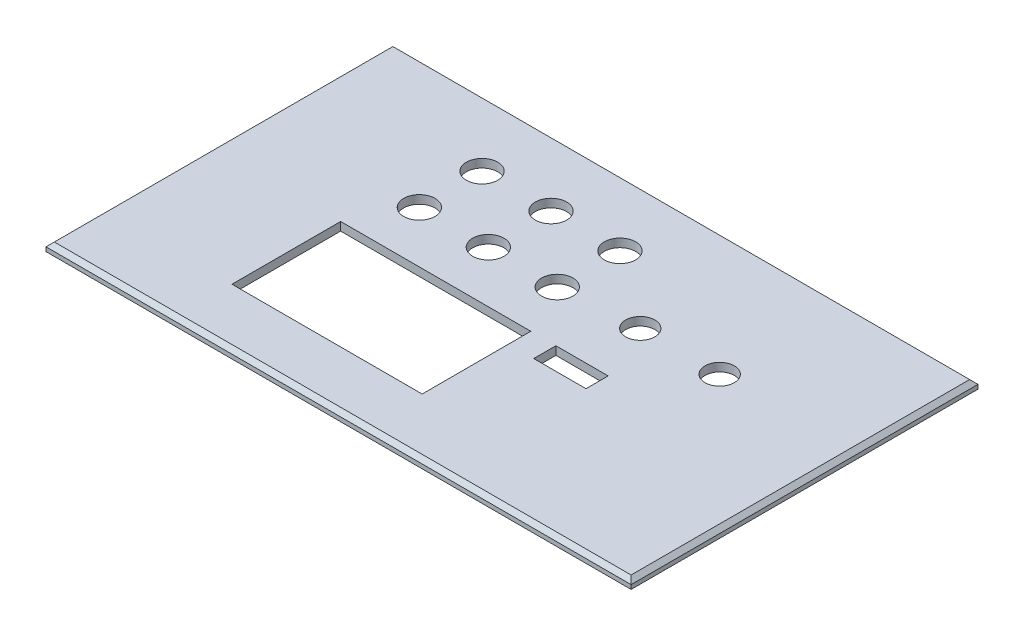
SolidWorks part; units mm, degrees
ref_plane "Front Plane" through (0, 0, 0) normal (0, 0, 1) x (1, 0, 0)
ref_plane "Top Plane" through (0, 0, 0) normal (0, 1, 0) x (1, 0, 0)
ref_plane "Right Plane" through (0, 0, 0) normal (1, 0, 0) x (0, 0, -1)
sketch "Sketch2" plane through (0, 0, 0) normal (0, 1, 0) x (1, 0, 0)
  line L1 (-53.6564, 31.1454) -> (-193.6564, 31.1454)
  line L2 (-53.6564, 31.1454) -> (-53.6564, -51.8546)
  line L3 (-53.6564, -51.8546) -> (-193.6564, -51.8546)
  line L4 (-193.6564, 31.1454) -> (-193.6564, -51.8546)
  line L13 (-162.6564, -38.3546) -> (-117.1564, -38.3546)
  line L14 (-162.6564, -38.3546) -> (-162.6564, -12.3546)
  line L15 (-162.6564, -12.3546) -> (-117.1564, -12.3546)
  line L16 (-117.1564, -38.3546) -> (-117.1564, -12.3546)
  line L19 (-98.6564, -17.6508) -> (-111.1564, -17.6508)
  line L20 (-98.6564, -17.6508) -> (-98.6564, -12.3508)
  line L21 (-98.6564, -12.3508) -> (-111.1564, -12.3508)
  line L22 (-111.1564, -17.6508) -> (-111.1564, -12.3508)
  circle A0 centre (-156.1564, 14.9775) radius 3.75
  circle A1 centre (-139.6564, 14.9775) radius 3.75
  circle A2 centre (-123.1564, 14.9775) radius 3.75
  circle A3 centre (-123.1564, -0.0225) radius 3.75
  circle A4 centre (-139.6564, -0.0225) radius 3.75
  circle A5 centre (-156.1564, -0.0225) radius 3.75
  circle A6 centre (-85.6564, 1.3396) radius 3.5
  circle A7 centre (-104.6564, 1.3396) radius 3.5
  point P4 (-123.6564, -10.3546)
  dimension "D3" = 7.5
  dimension "D4" = 16.5
  dimension "D7" = 6
  dimension "D8" = 7
  dimension "D11" = 19
  dimension "D1" = 140
  dimension "D2" = 83
  dimension "D5" = 16.5
  dimension "D6" = 15
extrude "Boss-Extrude1" add sketch "Sketch2" along normal blind 2
chamfer "Chamfer1" distance 1 angle 45 4 edges at (-193.6564, 2, 10.3546) (-123.6564, 2, 51.8546) (-53.6564, 2, 10.3546) (-123.6564, 2, -31.1454)
